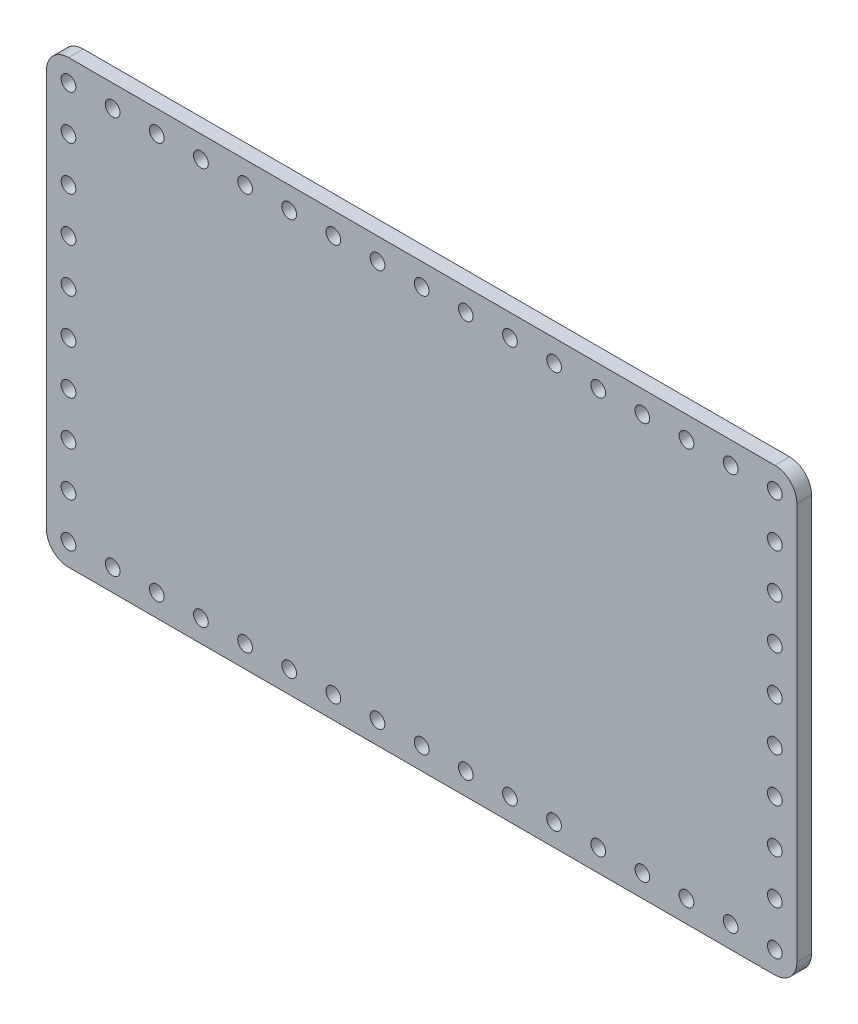
SolidWorks part; units mm, degrees
ref_plane "Alzado" through (0, 0, 0) normal (0, 0, 1) x (1, 0, 0)
ref_plane "Planta" through (0, 0, 0) normal (0, 1, 0) x (1, 0, 0)
ref_plane "Vista lateral" through (0, 0, 0) normal (1, 0, 0) x (0, 0, -1)
sketch "Model" plane through (0, 0, 0) normal (0, 0, 1) x (1, 0, 0)
  line L0 (404.9291, 485.2422) -> (404.9291, 404.2422)
  line L1 (256.4291, 489.7422) -> (400.4291, 489.7422)
  line L2 (256.4291, 399.7422) -> (400.4291, 399.7422)
  line L3 (251.9291, 485.2422) -> (251.9291, 404.2422)
  arc A0 (404.9291, 485.2422) -> (400.4291, 489.7422) centre (400.4291, 485.2422) ccw
  circle A1 centre (400.4291, 485.2422) radius 1.5
  circle A2 centre (400.4291, 476.2422) radius 1.5
  circle A3 centre (400.4291, 467.2422) radius 1.5
  circle A4 centre (400.4291, 458.2422) radius 1.5
  circle A5 centre (400.4291, 449.2422) radius 1.5
  circle A6 centre (400.4291, 440.2422) radius 1.5
  circle A7 centre (400.4291, 431.2422) radius 1.5
  circle A8 centre (400.4291, 422.2422) radius 1.5
  circle A9 centre (400.4291, 413.2422) radius 1.5
  circle A10 centre (400.4291, 404.2422) radius 1.5
  arc A11 (400.4291, 399.7422) -> (404.9291, 404.2422) centre (400.4291, 404.2422) ccw
  circle A12 centre (256.4291, 485.2422) radius 1.5
  circle A13 centre (256.4291, 476.2422) radius 1.5
  circle A14 centre (256.4291, 467.2422) radius 1.5
  circle A15 centre (256.4291, 458.2422) radius 1.5
  circle A16 centre (256.4291, 449.2422) radius 1.5
  circle A17 centre (256.4291, 440.2422) radius 1.5
  circle A18 centre (256.4291, 431.2422) radius 1.5
  circle A19 centre (256.4291, 422.2422) radius 1.5
  circle A20 centre (256.4291, 413.2422) radius 1.5
  circle A21 centre (256.4291, 404.2422) radius 1.5
  circle A22 centre (265.4291, 485.2422) radius 1.5
  circle A23 centre (265.4291, 404.2422) radius 1.5
  circle A24 centre (274.4291, 485.2422) radius 1.5
  circle A25 centre (274.4291, 404.2422) radius 1.5
  circle A26 centre (283.4291, 485.2422) radius 1.5
  circle A27 centre (283.4291, 404.2422) radius 1.5
  circle A28 centre (292.4291, 485.2422) radius 1.5
  circle A29 centre (292.4291, 404.2422) radius 1.5
  circle A30 centre (301.4291, 485.2422) radius 1.5
  circle A31 centre (301.4291, 404.2422) radius 1.5
  circle A32 centre (310.4291, 485.2422) radius 1.5
  circle A33 centre (310.4291, 404.2422) radius 1.5
  circle A34 centre (319.4291, 485.2422) radius 1.5
  circle A35 centre (319.4291, 404.2422) radius 1.5
  circle A36 centre (328.4291, 485.2422) radius 1.5
  circle A37 centre (328.4291, 404.2422) radius 1.5
  circle A38 centre (337.4291, 485.2422) radius 1.5
  circle A39 centre (337.4291, 404.2422) radius 1.5
  circle A40 centre (346.4291, 485.2422) radius 1.5
  circle A41 centre (346.4291, 404.2422) radius 1.5
  circle A42 centre (355.4291, 485.2422) radius 1.5
  circle A43 centre (355.4291, 404.2422) radius 1.5
  circle A44 centre (364.4291, 485.2422) radius 1.5
  circle A45 centre (364.4291, 404.2422) radius 1.5
  circle A46 centre (373.4291, 485.2422) radius 1.5
  circle A47 centre (373.4291, 404.2422) radius 1.5
  circle A48 centre (382.4291, 485.2422) radius 1.5
  circle A49 centre (382.4291, 404.2422) radius 1.5
  arc A50 (256.4291, 489.7422) -> (251.9291, 485.2422) centre (256.4291, 485.2422) ccw
  arc A51 (251.9291, 404.2422) -> (256.4291, 399.7422) centre (256.4291, 404.2422) ccw
  circle A52 centre (391.4291, 485.2422) radius 1.5
  circle A53 centre (391.4291, 404.2422) radius 1.5
extrude "Saliente-Extruir1" add sketch "Model" along normal blind 3
